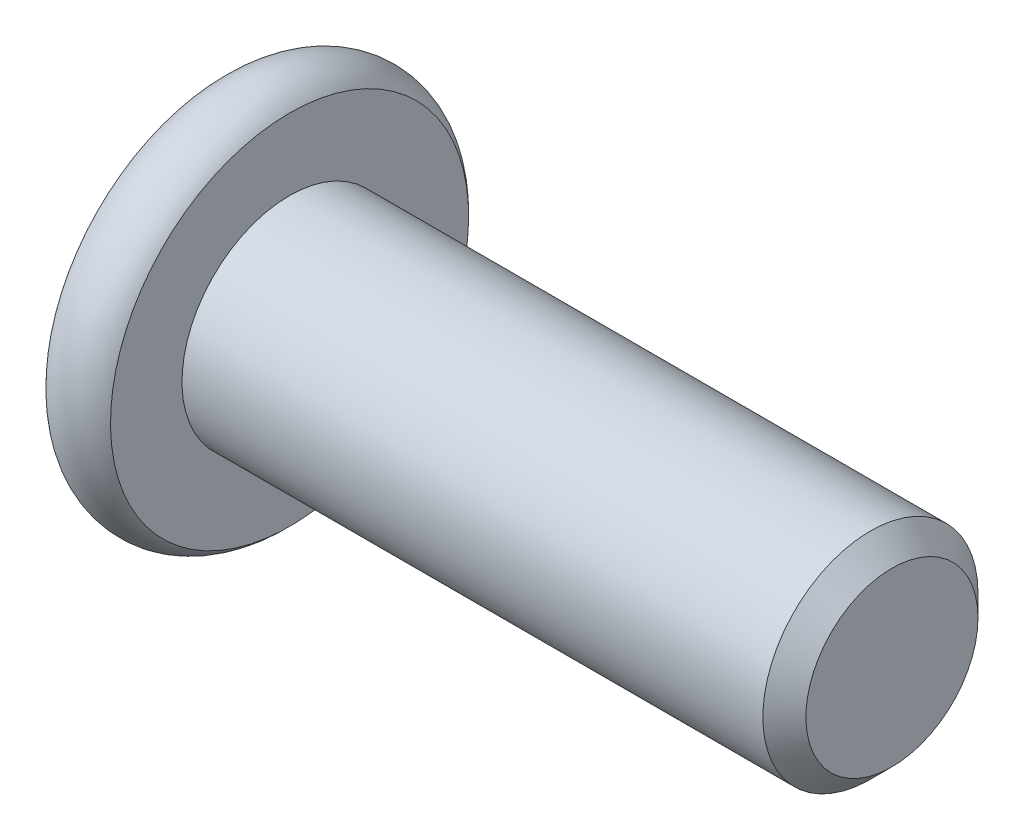
SolidWorks part; units mm, degrees
material "Plain Carbon Steel"
ref_plane "Front Plane" through (0, 0, 0) normal (0, 0, 1) x (1, 0, 0)
ref_plane "Top Plane" through (0, 0, 0) normal (0, 1, 0) x (1, 0, 0)
ref_plane "Right Plane" through (0, 0, 0) normal (1, 0, 0) x (0, 0, -1)
other "M5 x 15"
sketch "Sketch2" plane through (0, 0, 0) normal (1, 0, 0) x (0, 0, -1)
  circle A0 centre (0, 0) radius 2.5
  dimension "D1" = 5
extrude "Boss-Extrude1" add sketch "Sketch2" against normal blind 14
chamfer "Chamfer1" distance 0.5 angle 45 1 edges at (0, 0, -2.5)
sketch "Sketch6" plane through (0, 0, 0) normal (0, 0, 1) x (1, 0, 0)
  line L0 (-15.5, 0) -> (-15.5, 4.1614)
  line L1 (-15.5, 0) -> (-14, 0)
  line L2 (-14.75, 0) -> (-14.75, 3.5) construction
  line L6 (-14, 4.1614) -> (-14, 0)
  line L8 (-14, 0) -> (-14.6471, 0) construction
  line L10 (-14, 2.5) -> (-14, -2.5) construction
  arc A0 (-15.5, 4.1614) -> (-14, 4.1614) centre (-14.75, 3.5) cw
  dimension "D3" = 1
  dimension "D1" = 1.5
  dimension "D2" = 9
revolve "Revolve1" add sketch "Sketch6" angle 360 about L8
sketch "Sketch7" plane through (-15.5, 0, 0) normal (-1, 0, 0) x (0, 0, 1)
  line L1 (0, 1.7321) -> (-1.5, 0.866)
  line L2 (-1.5, 0.866) -> (-1.5, -0.866)
  line L3 (-1.5, -0.866) -> (0, -1.7321)
  line L4 (0, -1.7321) -> (1.5, -0.866)
  line L5 (1.5, -0.866) -> (1.5, 0.866)
  line L6 (1.5, 0.866) -> (0, 1.7321)
  circle A0 centre (0, 0) radius 1.5 construction
  dimension "D1" = 3
extrude "Cut-Extrude1" cut sketch "Sketch7" against normal blind 2.3
sketch "Sketch8" plane through (-15.5, 0, 0) normal (-1, 0, 0) x (0, 0, 1)
  circle A0 centre (0, 0) radius 1.7821
  dimension "D1" = 0.05
extrude "Cut-Extrude2" cut sketch "Sketch8" against normal blind 1 draft 45
